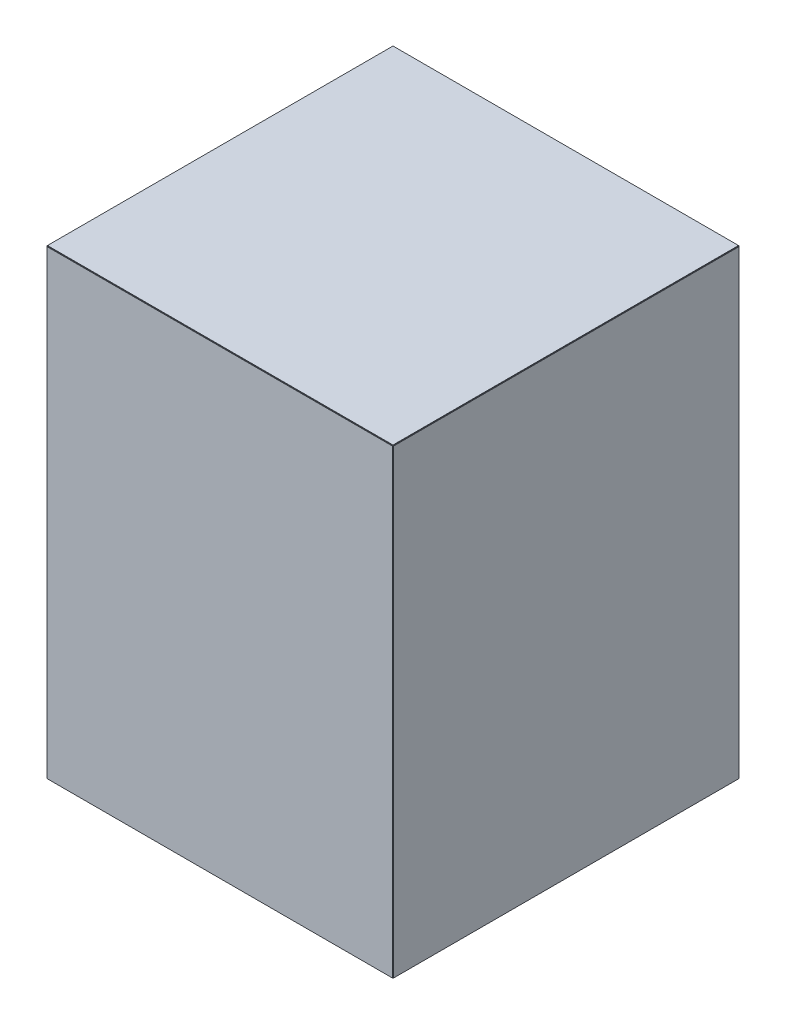
SolidWorks part; units mm, degrees
ref_plane "Front" through (0, 0, 0) normal (0, 0, 1) x (1, 0, 0)
ref_plane "Top" through (0, 0, 0) normal (0, 1, 0) x (1, 0, 0)
ref_plane "Right" through (0, 0, 0) normal (1, 0, 0) x (0, 0, -1)
sketch3d "3DSketch1"
  line L0 (-914.4, 0, 0) -> (914.4, 0, 0) construction
  line L1 (0, 0, -914.4) -> (0, 0, 914.4) construction
  line L3 (-914.4, 1219.2, -914.4) -> (914.4, 1219.2, -914.4)
  line L4 (-914.4, 1219.2, -914.4) -> (-914.4, -1219.2, -914.4)
  line L5 (-914.4, -1219.2, -914.4) -> (914.4, -1219.2, -914.4)
  line L6 (914.4, 1219.2, -914.4) -> (914.4, -1219.2, -914.4)
  line L7 (-914.4, 1219.2, -914.4) -> (914.4, -1219.2, -914.4) construction
  line L8 (-914.4, -1219.2, -914.4) -> (914.4, 1219.2, -914.4) construction
  line L13 (914.4, -1219.2, 914.4) -> (914.4, 1219.2, 914.4)
  line L14 (914.4, -1219.2, 914.4) -> (914.4, -1219.2, -914.4)
  line L15 (914.4, -1219.2, -914.4) -> (914.4, 1219.2, -914.4) construction
  line L16 (914.4, 1219.2, 914.4) -> (914.4, 1219.2, -914.4)
  line L17 (914.4, -1219.2, 914.4) -> (914.4, 1219.2, -914.4) construction
  line L18 (914.4, -1219.2, -914.4) -> (914.4, 1219.2, 914.4) construction
  line L19 (-914.4, -1219.2, 914.4) -> (914.4, -1219.2, 914.4)
  line L20 (-914.4, -1219.2, 914.4) -> (-914.4, 1219.2, 914.4)
  line L21 (-914.4, 1219.2, 914.4) -> (914.4, 1219.2, 914.4)
  line L22 (914.4, -1219.2, 914.4) -> (914.4, 1219.2, 914.4) construction
  line L23 (-914.4, -1219.2, 914.4) -> (914.4, 1219.2, 914.4) construction
  line L24 (-914.4, 1219.2, 914.4) -> (914.4, -1219.2, 914.4) construction
  line L25 (-914.4, -1219.2, -914.4) -> (-914.4, 1219.2, -914.4) construction
  line L26 (-914.4, -1219.2, -914.4) -> (-914.4, -1219.2, 914.4)
  line L27 (-914.4, -1219.2, 914.4) -> (-914.4, 1219.2, 914.4) construction
  line L28 (-914.4, 1219.2, -914.4) -> (-914.4, 1219.2, 914.4)
  line L29 (-914.4, -1219.2, -914.4) -> (-914.4, 1219.2, 914.4) construction
  line L30 (-914.4, -1219.2, 914.4) -> (-914.4, 1219.2, -914.4) construction
  line L31 (914.4, -1219.2, 914.4) -> (-914.4, -1219.2, -914.4) construction
  line L32 (-914.4, 1219.2, -914.4) -> (914.4, 1219.2, 914.4) construction
  line L33 (-914.4, 1219.2, 914.4) -> (914.4, 1219.2, -914.4) construction
  line L34 (914.4, -1219.2, -914.4) -> (-914.4, -1219.2, 914.4) construction
  line L35 (0, 1219.2, 0) -> (0, -1219.2, 0) construction
  point P5 (0, 0, 0)
  point P8 (0, 0, 0)
  point P21 (0, 0, 0)
  point P22 (0, 0, 0)
  dimension "D1" = 1828.8
  dimension "D2" = 1828.8
  dimension "D3" = 2438.4
ref_plane "Plane11" through (0, 1219.2, 0) normal (0, 1, 0) x (1, 0, 0)
sketch "Sketch14" plane through (0, 1219.2, 0) normal (0, 1, 0) x (1, 0, 0)
  line L1 (914.4, 914.4) -> (-914.4, 914.4)
  line L2 (914.4, 914.4) -> (914.4, -914.4)
  line L3 (914.4, -914.4) -> (-914.4, -914.4)
  line L4 (-914.4, 914.4) -> (-914.4, -914.4)
  line L5 (914.4, 914.4) -> (-914.4, -914.4) construction
  line L6 (914.4, -914.4) -> (-914.4, 914.4) construction
  point P0 (0, 0)
extrude "Boss-Extrude20" add sketch "Sketch14" along normal blind 3.175
ref_plane "Plane10" through (0, 0, -914.4) normal (0, 0, -1) x (-1, 0, 0)
sketch "Sketch13" plane through (0, 0, -914.4) normal (0, 0, -1) x (-1, 0, 0)
  line L1 (-914.4, -1219.2) -> (914.4, -1219.2)
  line L2 (-914.4, -1219.2) -> (-914.4, 1219.2)
  line L3 (-914.4, 1219.2) -> (914.4, 1219.2)
  line L4 (914.4, -1219.2) -> (914.4, 1219.2)
  line L5 (-914.4, -1219.2) -> (914.4, 1219.2) construction
  line L6 (-914.4, 1219.2) -> (914.4, -1219.2) construction
  point P0 (0, 0)
extrude " Illuminance Plane 1-15-2019 3:02:36 PM" add sketch "Sketch13" along normal blind 3.175
ref_plane "Plane9" through (-914.4, 0, 0) normal (-1, 0, 0) x (0, 0, 1)
sketch "Sketch12" plane through (-914.4, 0, 0) normal (-1, 0, 0) x (0, 0, 1)
  line L1 (-914.4, -1219.2) -> (914.4, -1219.2)
  line L2 (-914.4, -1219.2) -> (-914.4, 1219.2)
  line L3 (-914.4, 1219.2) -> (914.4, 1219.2)
  line L4 (914.4, -1219.2) -> (914.4, 1219.2)
  line L5 (-914.4, -1219.2) -> (914.4, 1219.2) construction
  line L6 (-914.4, 1219.2) -> (914.4, -1219.2) construction
  point P0 (0, 0)
extrude "Boss-Extrude18" add sketch "Sketch12" along normal blind 3.175
ref_plane "Plane8" through (914.4, 0, 0) normal (1, 0, 0) x (0, 0, -1)
sketch "Sketch11" plane through (914.4, 0, 0) normal (1, 0, 0) x (0, 0, -1)
  line L1 (-914.4, -1219.2) -> (914.4, -1219.2)
  line L2 (-914.4, -1219.2) -> (-914.4, 1219.2)
  line L3 (-914.4, 1219.2) -> (914.4, 1219.2)
  line L4 (914.4, -1219.2) -> (914.4, 1219.2)
  line L5 (-914.4, -1219.2) -> (914.4, 1219.2) construction
  line L6 (-914.4, 1219.2) -> (914.4, -1219.2) construction
  point P0 (0, 0)
extrude "Boss-Extrude16" add sketch "Sketch11" along normal blind 3.175
ref_plane "Plane2" through (0, 0, 914.4) normal (0, 0, 1) x (1, 0, 0)
sketch "Sketch2" plane through (0, 0, 914.4) normal (0, 0, 1) x (1, 0, 0)
  line L1 (-914.4, -1219.2) -> (914.4, -1219.2)
  line L2 (-914.4, -1219.2) -> (-914.4, 1219.2)
  line L3 (-914.4, 1219.2) -> (914.4, 1219.2)
  line L4 (914.4, -1219.2) -> (914.4, 1219.2)
  line L5 (-914.4, -1219.2) -> (914.4, 1219.2) construction
  line L6 (-914.4, 1219.2) -> (914.4, -1219.2) construction
  point P0 (0, 0)
extrude "Boss-Extrude5" add sketch "Sketch2" along normal blind 3.175
equation "\"width\"= 6ft"
equation "\"D1@3DSketch1\"=\"width\""
equation "\"depth\"= 6ft"
equation "\"D2@3DSketch1\"=\"depth\""
equation "\"height\"= 8ft"
equation "\"D3@3DSketch1\"=\"height\""
equation "\"wall\"=0.125"
equation "\"D1@Boss-Extrude5\"=\"wall\""
equation "\"D1@Boss-Extrude16\"=\"wall\""
equation "\"D1@Boss-Extrude18\"=\"wall\""
equation "\"D1@ Illuminance Plane 1-15-2019 3:02:36 PM\"=\"wall\""
equation "\"D1@Boss-Extrude20\"=\"wall\""
